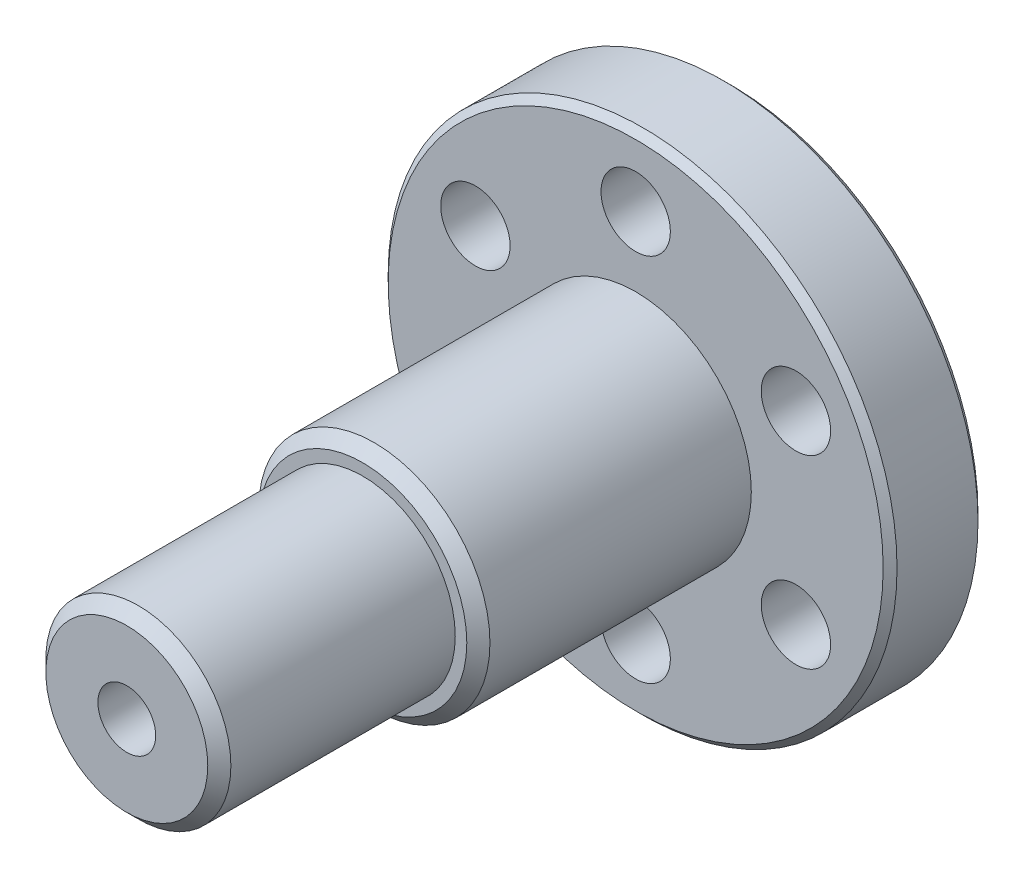
SolidWorks part; units mm, degrees
material "6061 合金"
ref_plane "前视基准面" through (0, 0, 0) normal (0, 0, 1) x (1, 0, 0)
ref_plane "上视基准面" through (0, 0, 0) normal (0, 1, 0) x (1, 0, 0)
ref_plane "右视基准面" through (0, 0, 0) normal (1, 0, 0) x (0, 0, -1)
sketch "草图1" plane through (0, 0, 0) normal (0, 0, 1) x (1, 0, 0)
  circle A0 centre (0, 0) radius 8 construction
  circle A1 centre (0, 0) radius 11
  circle A2 centre (0, 8) radius 1.5
  circle A3 centre (6.9282, 4) radius 1.5
  circle A4 centre (6.9282, -4) radius 1.5
  circle A5 centre (0, -8) radius 1.5
  circle A6 centre (-6.9282, -4) radius 1.5
  circle A7 centre (-6.9282, 4) radius 1.5
  point P19 (0, 0)
  dimension "D1" = 16
  dimension "D2" = 3
  dimension "D3" = 3
  dimension "D4" = 6
extrude "凸台-拉伸1" add sketch "草图1" along normal blind 4.1
sketch "草图2" plane through (0, 0, 4.1) normal (0, 0, 1) x (1, 0, 0)
  circle A0 centre (0, 0) radius 5
  dimension "D1" = 10
extrude "凸台-拉伸2" add sketch "草图2" along normal blind 22
sketch "草图3" plane through (0, 0, 26.1) normal (0, 0, 1) x (1, 0, 0)
  circle A0 centre (0, 0) radius 4
  dimension "D1" = 8
extrude "切除-拉伸1" cut sketch "草图3" against normal offset from surface (10.2 mm away) 11.8 flip side to cut up to face at (5, 0, 4.1)
chamfer "倒角1" distance 0.5 angle 45 2 edges at (4, 0, 26.1) (5, 0, 15.9)
hole_wizard "M3 螺纹孔1" positions "草图4" profile "草图5" tap size "M3" standard "GB"
sketch "草图4" plane through (0, 0, 26.1) normal (0, 0, 1) x (1, 0, 0)
  point P0 (0, 0)
sketch "草图5" plane through (0, 0, 26.1) normal (1, 0, 0) x (0, -1, 0)
  line L0 (0, 0) -> (0, 10.2511)
  line L1 (0, 10.2511) -> (1.25, 9.5)
  line L2 (1.25, 9.5) -> (1.25, 0)
  line L5 (1.25, 0) -> (0, 0)
  line L10 (0, 10.2511) -> (-1.25, 9.5) construction
  line L11 (0, -6.35) -> (0, 107.95) construction
  dimension "螺纹孔钻头直径" = 2.5
  dimension "螺纹孔钻头深度" = 9.5
  dimension "导头角度" = 118
cosmetic thread "孔螺蚊线1" parameters "D1"=8, "D2"=3
chamfer "倒角2" distance 0.3 angle 45 2 edges at (11, 0, 4.1) (11, 0, 0)
